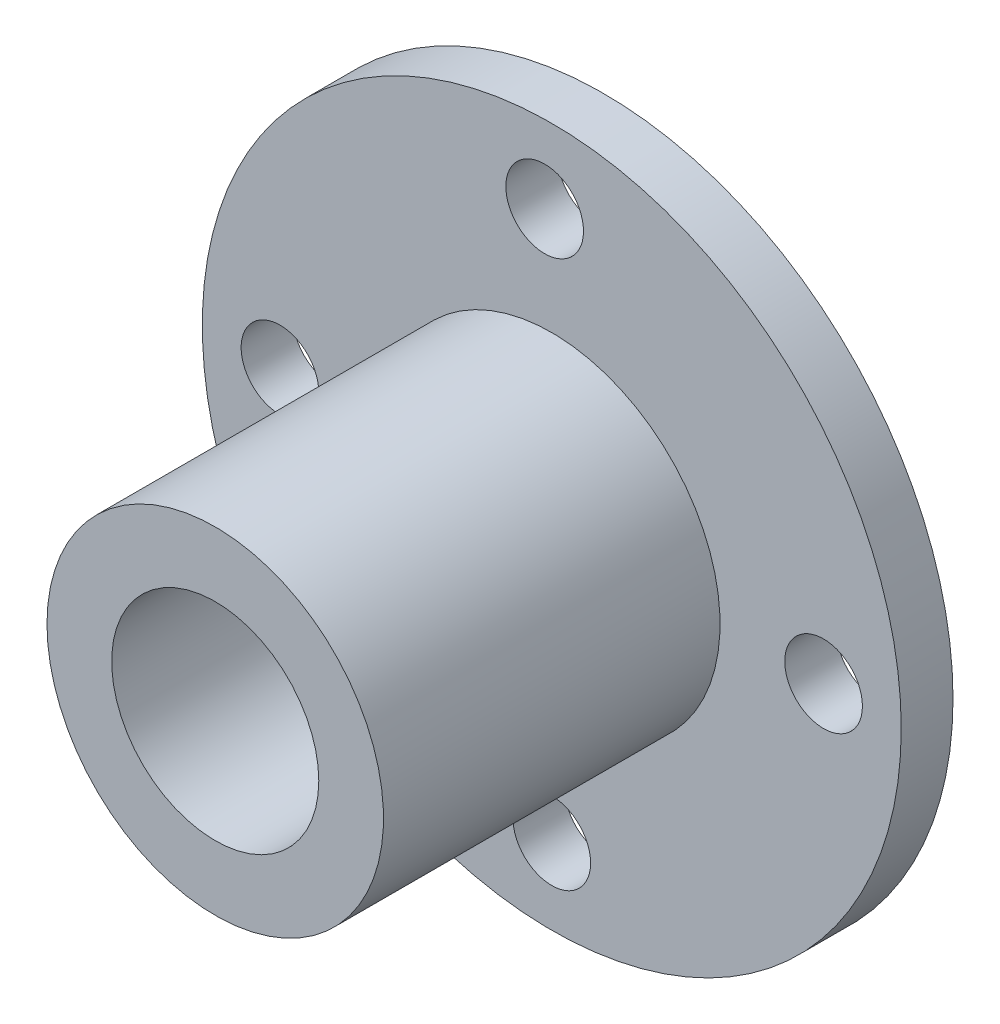
SolidWorks part; units mm, degrees
material "1060 合金"
ref_plane "前视基准面" through (0, 0, 0) normal (0, 0, 1) x (1, 0, 0)
ref_plane "上视基准面" through (0, 0, 0) normal (0, 1, 0) x (1, 0, 0)
ref_plane "右视基准面" through (0, 0, 0) normal (1, 0, 0) x (0, 0, -1)
other "Configuration Table"
sketch "草图1" plane through (0, 0, 0) normal (0, 0, 1) x (1, 0, 0)
  circle A0 centre (0, 0) radius 13.5
extrude "凸台-拉伸1" add sketch "草图1" along normal blind 2
sketch "草图2" plane through (0, 0, 2) normal (0, 0, 1) x (1, 0, 0)
  circle A0 centre (0, 0) radius 6.5
extrude "凸台-拉伸2" add sketch "草图2" along normal blind 13
sketch "草图3" plane through (0, 0, 15) normal (0, 0, 1) x (1, 0, 0)
  circle A0 centre (0, 0) radius 4
extrude "切除-拉伸1" cut sketch "草图3" against normal blind 15
sketch "草图4" plane through (0, 0, 2) normal (0, 0, 1) x (1, 0, 0)
  circle A0 centre (0, 0) radius 13.5 construction
  circle A2 centre (-10.5, 0) radius 1.5
  circle A3 centre (-0.2747, 10.5) radius 1.5
  circle A4 centre (10.5, 0) radius 1.5
  circle A5 centre (0, -10.5) radius 1.5
  point P0 (-10.5, 0)
  point P3 (-0.2747, 10.5)
  point P4 (0, -10.5)
  point P5 (10.5, 0)
  dimension "D1" = 10.5
  dimension "D2" = 10.5
  dimension "D3" = 10.5
  dimension "D4" = 10.5
extrude "切除-拉伸2" cut sketch "草图4" against normal blind 15
